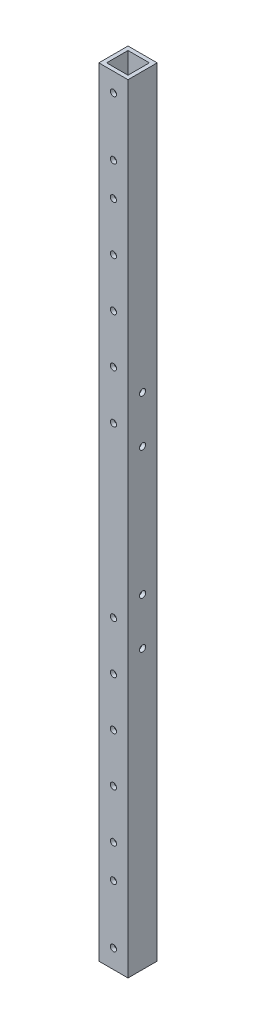
SolidWorks part; units mm, degrees
ref_plane "Front Plane" through (0, 0, 0) normal (0, 0, 1) x (1, 0, 0)
ref_plane "Top Plane" through (0, 0, 0) normal (0, 1, 0) x (1, 0, 0)
ref_plane "Right Plane" through (0, 0, 0) normal (1, 0, 0) x (0, 0, -1)
sketch "Sketch1" plane through (0, 0, 0) normal (0, 1, 0) x (1, 0, 0)
  line L0 (2, 2) -> (2, 13)
  line L1 (0, 0) -> (15, 0)
  line L2 (0, 0) -> (0, 15)
  line L3 (0, 15) -> (15, 15)
  line L4 (15, 0) -> (15, 15)
  line L5 (2, 13) -> (13, 13)
  line L6 (13, 2) -> (13, 13)
  line L7 (2, 2) -> (13, 2)
  dimension "D1" = 15
  dimension "D2" = 2
extrude "Boss-Extrude1" add sketch "Sketch1" along normal blind 400
sketch "Sketch2" plane through (0, 0, 0) normal (0, 0, 1) x (1, 0, 0)
  line L0 (0, 200) -> (15, 200) construction
  line L1 (0, 400) -> (0, 0) construction
  line L2 (15, 400) -> (15, 0) construction
  circle A0 centre (7.5, 9.6) radius 1.6
  circle A1 centre (7.5, 39.6) radius 1.6
  circle A2 centre (7.5, 56.7) radius 1.6
  circle A3 centre (7.5, 81.7) radius 1.6
  circle A4 centre (7.5, 106.7) radius 1.6
  circle A5 centre (7.5, 131.7) radius 1.6
  circle A6 centre (7.5, 156.7) radius 1.6
  circle A7 centre (7.5, 243.3) radius 1.6
  circle A8 centre (7.5, 268.3) radius 1.6
  circle A9 centre (7.5, 293.3) radius 1.6
  circle A10 centre (7.5, 318.3) radius 1.6
  circle A11 centre (7.5, 343.3) radius 1.6
  circle A12 centre (7.5, 360.4) radius 1.6
  circle A13 centre (7.5, 390.4) radius 1.6
  dimension "D1" = 3.2
extrude "Cut-Extrude1" cut sketch "Sketch2" against normal through all
sketch "Sketch3" plane through (15, 0, 0) normal (1, 0, 0) x (0, 0, -1)
  circle A0 centre (7.5, 143) radius 1.6
  circle A1 centre (7.5, 167) radius 1.6
  circle A2 centre (7.5, 233) radius 1.6
  circle A3 centre (7.5, 257) radius 1.6
  dimension "D1" = 3.2
extrude "Cut-Extrude2" cut sketch "Sketch3" against normal through all
